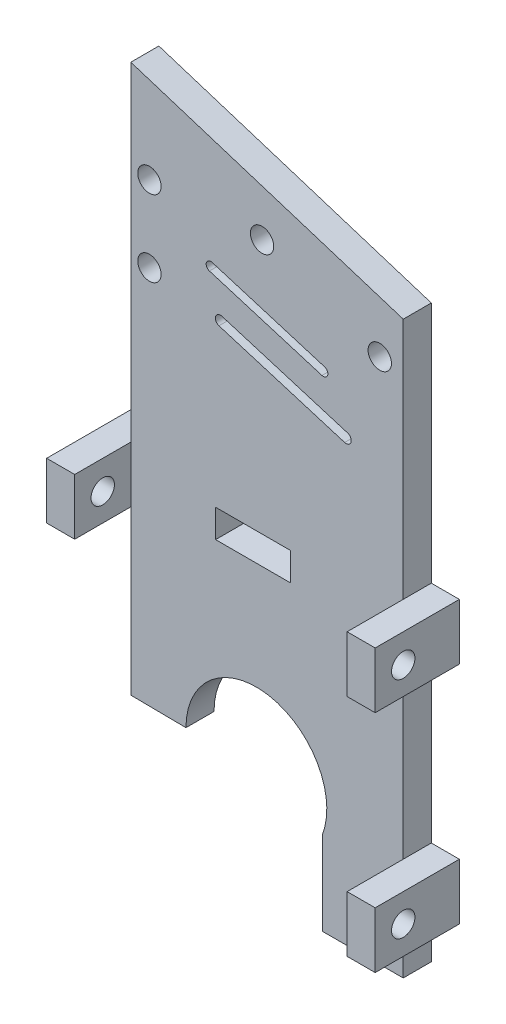
SolidWorks part; units mm, degrees
ref_plane "Front Plane" through (0, 0, 0) normal (0, 0, 1) x (1, 0, 0)
ref_plane "Top Plane" through (0, 0, 0) normal (0, 1, 0) x (1, 0, 0)
ref_plane "Right Plane" through (0, 0, 0) normal (1, 0, 0) x (0, 0, -1)
sketch "Sketch1" plane through (0, 0, 0) normal (0, 1, 0) x (1, 0, 0)
  line L1 (-50.1455, -21.689) -> (-21.0155, -21.689)
  line L2 (-50.1455, -21.689) -> (-50.1455, -23.689)
  line L3 (-50.1455, -23.689) -> (-21.0155, -23.689)
  line L4 (-21.0155, -21.689) -> (-21.0155, -23.689)
extrude "Boss-Extrude1" add sketch "Sketch1" along normal blind 45.22
sketch "Sketch15" plane through (0, 0, 0) normal (0, -1, 0) x (1, 0, 0)
  line L0 (-21.0155, 23.689) -> (-28.6855, 23.689) construction
  line L1 (-28.6855, 23.689) -> (-24.8505, 23.689) construction
  line L2 (-24.8505, 23.689) -> (-24.8505, 21.689) construction
  line L4 (-24.8505, 21.689) -> (-21.0155, 21.689) construction
  line L6 (-24.8505, 23.689) -> (-21.0155, 23.689)
  line L7 (-24.8505, 23.689) -> (-24.8505, 21.689)
  line L8 (-24.8505, 21.689) -> (-21.0155, 21.689)
  line L9 (-21.0155, 23.689) -> (-21.0155, 21.689)
extrude "Boss-Extrude7" add sketch "Sketch15" along normal blind 25.02
sketch "Sketch19" plane through (-21.0155, 0, 0) normal (1, 0, 0) x (0, 0, -1)
  line L0 (-23.689, -14.02) -> (-21.689, -14.02) construction
  line L2 (-21.689, -14.02) -> (-21.689, -20.02)
  line L3 (-23.689, -20.02) -> (-21.689, -20.02)
  line L5 (-23.689, -14.02) -> (-21.689, -14.02)
  line L6 (-23.689, -14.02) -> (-23.689, -20.02)
extrude "Boss-Extrude9" add sketch "Sketch19" along normal blind 3
sketch "Sketch20" plane through (0, 0, 21.689) normal (0, 0, -1) x (-1, 0, 0)
  line L1 (18.0155, -14.02) -> (21.0155, -14.02)
  line L2 (18.0155, -14.02) -> (18.0155, -20.02)
  line L3 (18.0155, -20.02) -> (21.0155, -20.02)
  line L4 (21.0155, -14.02) -> (21.0155, -20.02)
extrude "Boss-Extrude10" add sketch "Sketch20" along normal blind 6
sketch "Sketch24" plane through (0, 0, 23.689) normal (0, 0, 1) x (1, 0, 0)
  line L0 (-21.0155, 45.22) -> (-21.0155, 37.57) construction
  line L1 (-21.0155, 45.22) -> (-21.0155, -14.02) construction
  line L2 (-21.0155, 45.22) -> (-21.0155, 37.57)
  line L3 (-21.0155, 37.57) -> (-50.1455, 45.22)
  line L4 (-50.1455, 45.22) -> (-21.0155, 45.22)
  line L5 (-21.0155, 45.22) -> (-21.0155, -14.02) construction
  line L6 (-50.1455, 45.22) -> (-21.0155, 45.22) construction
  line L8 (-21.0155, 45.22) -> (-21.0155, 37.57) construction
extrude "Cut-Extrude10" cut sketch "Sketch24" against normal blind 4
sketch "Sketch27" plane through (0, 0, 23.689) normal (0, 0, 1) x (1, 0, 0)
  circle A0 centre (-48.1555, 35.3258) radius 1.25
  circle A1 centre (-48.1555, 27.1812) radius 1.25
extrude "Cut-Extrude13" cut sketch "Sketch27" against normal blind 5
sketch "Sketch28" plane through (0, 0, 23.689) normal (0, 0, 1) x (1, 0, 0)
  line L0 (-48.1592, 35.3258) -> (-48.1592, 27.1812) construction
  line L1 (-48.1592, 27.1812) -> (-48.1592, 31.2535) construction
  line L2 (-48.1592, 31.2535) -> (-23.5255, 31.2535) construction
  circle A0 centre (-23.5255, 31.2535) radius 1.25
sketch "Sketch32" plane through (0, 0, 23.689) normal (0, 0, 1) x (1, 0, 0)
  circle A0 centre (-36.1145, 35.7898) radius 1.25
sketch "Sketch35" plane through (0, 0, 23.689) normal (0, 0, 1) x (1, 0, 0)
  line L0 (-21.0155, 37.57) -> (-21.0155, 35.99)
  line L1 (-21.0155, 37.57) -> (-21.0155, -14.02) construction
  line L2 (-21.0155, 35.99) -> (-21.0155, 37.57)
  line L3 (-21.0155, 35.99) -> (-50.1455, 45.22)
  line L4 (-50.1455, 45.22) -> (-21.0155, 37.57)
  line M5 (-21.0155, -14.02) -> (-21.0155, 37.57)
  line M6 (-21.0155, 37.57) -> (-50.1455, 45.22)
extrude "Cut-Extrude16" cut sketch "Sketch35" against normal blind 4.86 contours L3 M5 M6
mirror "Mirror1" about plane through (0, 0, 15.689) normal (0, 0, -1) of bodies 129 130
delete or keep bodies "Body-Delete/Keep 1" type delete bodies bodies 129
sketch "Sketch37" plane through (0, 0, 7.689) normal (0, 0, -1) x (-1, 0, 0)
  line L13 (21.0155, 24.3006) -> (50.1455, 33.1563) construction
  line L14 (29.5652, 26.8997) -> (41.5958, 30.5571) construction
  line L15 (29.4224, 27.3694) -> (41.453, 31.0268)
  line L16 (29.708, 26.4301) -> (41.7386, 30.0874)
  line L17 (21.0155, 24.3006) -> (21.0155, 20.1026) construction
  line L18 (21.0155, 20.1026) -> (50.1455, 28.9583) construction
  line L19 (27.1219, 21.959) -> (40.5639, 26.0454) construction
  line L20 (26.9639, 22.4788) -> (40.4059, 26.5653)
  line L21 (27.28, 21.4391) -> (40.722, 25.5256)
  arc A0 (29.4224, 27.3694) -> (29.708, 26.4301) centre (29.5652, 26.8997) ccw
  arc A1 (41.7386, 30.0874) -> (41.453, 31.0268) centre (41.5958, 30.5571) ccw
  arc A2 (26.9639, 22.4788) -> (27.28, 21.4391) centre (27.1219, 21.959) ccw
  arc A3 (40.722, 25.5256) -> (40.4059, 26.5653) centre (40.5639, 26.0454) ccw
  point P18 (35.5805, 28.7284)
  point P27 (33.8429, 24.0022)
extrude "Cut-Extrude20" cut sketch "Sketch37" against normal blind 5
mirror "Mirror2" about plane through (0, 0, 15.689) normal (0, 0, 1) of bodies 134
delete or keep bodies "Body-Delete/Keep 2" type delete bodies bodies 134
extrude "Cut-Extrude23" cut sketch "Sketch28" against normal blind 5 contours A0
extrude "Cut-Extrude25" cut sketch "Sketch32" against normal blind 5 contours A0
sketch "Sketch38" plane through (-50.1455, 0, 0) normal (-1, 0, 0) x (0, 0, 1)
  line L0 (23.689, 4.0427) -> (23.689, 3.98) construction
  line L1 (21.689, 4.0427) -> (23.689, 4.0427)
  line L2 (21.689, 4.0427) -> (21.689, 10.0427)
  line L3 (21.689, 10.0427) -> (23.689, 10.0427)
  line L4 (23.689, 4.0427) -> (23.689, 10.0427)
  line L5 (23.689, 45.22) -> (23.689, 0) construction
  line L6 (23.689, 10.0427) -> (23.689, 9.98) construction
extrude "Boss-Extrude11" add sketch "Sketch38" along normal blind 3
sketch "Sketch39" plane through (0, 0, 21.689) normal (0, 0, -1) x (-1, 0, 0)
  line L1 (53.1455, 10.0427) -> (50.1455, 10.0427)
  line L2 (53.1455, 10.0427) -> (53.1455, 4.0427)
  line L3 (53.1455, 4.0427) -> (50.1455, 4.0427)
  line L4 (50.1455, 10.0427) -> (50.1455, 4.0427)
extrude "Boss-Extrude12" add sketch "Sketch39" along normal blind 6
sketch "Sketch40" plane through (-53.1455, 0, 0) normal (-1, 0, 0) x (0, 0, 1)
  line L0 (15.689, 4.0427) -> (15.689, 7.0427) construction
  line L1 (15.689, 4.0427) -> (15.689, 10.0427) construction
  circle A0 centre (18.689, 6.98) radius 1.25
extrude "Cut-Extrude26" cut sketch "Sketch40" against normal blind 6
sketch "Sketch51" plane through (-21.0155, 0, 0) normal (1, 0, 0) x (0, 0, -1)
  line L0 (-23.689, 4.0427) -> (-21.689, 4.0427) construction
  line L1 (-21.689, 35.99) -> (-21.689, -14.02) construction
  line L3 (-23.689, 4.0427) -> (-21.689, 4.0427)
  line L4 (-23.689, 4.0427) -> (-23.689, 10.0427)
  line L5 (-23.689, 10.0427) -> (-21.689, 10.0427)
  line L6 (-21.689, 4.0427) -> (-21.689, 10.0427)
extrude "Boss-Extrude15" add sketch "Sketch51" along normal blind 3
sketch "Sketch52" plane through (0, 0, 21.689) normal (0, 0, -1) x (-1, 0, 0)
  line L1 (18.0155, 10.0427) -> (21.0155, 10.0427)
  line L2 (18.0155, 10.0427) -> (18.0155, 4.0427)
  line L3 (18.0155, 4.0427) -> (21.0155, 4.0427)
  line L4 (21.0155, 10.0427) -> (21.0155, 4.0427)
extrude "Boss-Extrude16" add sketch "Sketch52" along normal blind 6
sketch "Sketch53" plane through (-18.0155, 0, 0) normal (1, 0, 0) x (0, 0, -1)
  line L0 (-23.689, 7.0427) -> (-15.689, 7.0427) construction
  line L1 (-23.689, 10.0427) -> (-23.689, 4.0427) construction
  line L2 (-15.689, 10.0427) -> (-15.689, 4.0427) construction
  line L3 (-15.689, 7.0427) -> (-21.689, 7.0427) construction
  circle A0 centre (-18.689, 6.98) radius 1.25
extrude "Cut-Extrude28" cut sketch "Sketch53" against normal blind 6 contours A0
mirror "Mirror4" about plane through (0, 0, 15.689) normal (0, 0, -1) of bodies 150
delete or keep bodies "Body-Delete/Keep 3" type delete bodies bodies 150
sketch "Sketch54" plane through (-18.0155, 0, 0) normal (1, 0, 0) x (0, 0, -1)
  circle A0 centre (-12.689, -17.012) radius 1.25
extrude "Cut-Extrude29" cut sketch "Sketch54" against normal blind 3
sketch "Sketch55" plane through (0, 0, 7.689) normal (0, 0, -1) x (-1, 0, 0)
  line L0 (24.8505, 0) -> (21.0155, -25.02)
  line L1 (21.0155, -25.02) -> (24.8505, -25.02)
  line L2 (24.8505, -25.02) -> (24.8505, 0)
extrude "Cut-Extrude30" cut sketch "Sketch55" against normal blind 10
sketch "Sketch56" plane through (0, 0, 9.689) normal (0, 0, 1) x (1, 0, 0)
  line L0 (-24.8505, 0) -> (-36.7178, -13.4588) construction
  line L1 (-50.1455, 0) -> (-50.1455, -13.393)
  line L2 (-50.1455, -13.393) -> (-44.2488, -13.4588)
  line L3 (-21.0155, -25.02) -> (-29.6598, -25.02)
  line L4 (-29.6598, -25.02) -> (-29.6598, -16.0856)
  circle A0 centre (-36.7178, -13.4588) radius 7.531
extrude "Boss-Extrude17" add sketch "Sketch56" against normal blind 3
sketch "Sketch57" plane through (0, 0, 7.689) normal (0, 0, -1) x (-1, 0, 0)
  line L0 (21.0155, -25.02) -> (21.0155, -20.02)
  line L1 (21.0155, -20.02) -> (18.0155, -20.02)
  line L2 (18.0155, -20.02) -> (18.0155, -14.02)
  line L3 (18.0155, -14.02) -> (21.0155, -14.02)
  line L4 (21.0155, -14.02) -> (21.0155, 4.0427)
  line L5 (21.0155, 4.0427) -> (18.0155, 4.0427)
  line L6 (18.0155, 4.0427) -> (18.0155, 10.0427)
  line L7 (18.0155, 10.0427) -> (21.0155, 10.0427)
  line L8 (21.0155, 10.0427) -> (21.0155, 35.99)
  line L9 (21.0155, 35.99) -> (50.1455, 45.22)
  line L10 (50.1455, 45.22) -> (50.1455, 10.0427)
  line L11 (50.1455, 10.0427) -> (53.1455, 10.0427)
  line L12 (53.1455, 10.0427) -> (53.1455, 4.0427)
  line L13 (53.1455, 4.0427) -> (50.1455, 4.0427)
  line L14 (50.1455, 4.0427) -> (50.1455, 0)
  line L15 (50.1455, 0) -> (24.8505, 0)
  line L16 (24.8505, 0) -> (21.0155, -25.02)
  line L17 (29.5652, 26.8997) -> (41.5958, 30.5571) construction
  line L18 (29.4229, 27.3679) -> (41.4535, 31.0253)
  line L19 (29.7075, 26.4316) -> (41.7381, 30.0889)
  line L20 (27.1219, 21.959) -> (40.5639, 26.0454) construction
  line L21 (26.964, 22.4783) -> (40.4061, 26.5648)
  line L22 (27.2798, 21.4396) -> (40.7218, 25.5261)
  circle A0 centre (23.5255, 31.2535) radius 1.25
  circle A1 centre (36.1145, 35.7898) radius 1.25
  circle A2 centre (48.1555, 35.3258) radius 1.25
  circle A3 centre (48.1555, 27.1812) radius 1.25
  arc A4 (29.4229, 27.3679) -> (29.7075, 26.4316) centre (29.5652, 26.8997) ccw
  arc A5 (41.7381, 30.0889) -> (41.4535, 31.0253) centre (41.5958, 30.5571) ccw
  arc A6 (26.964, 22.4783) -> (27.2798, 21.4396) centre (27.1219, 21.959) ccw
  arc A7 (40.7218, 25.5261) -> (40.4061, 26.5648) centre (40.5639, 26.0454) ccw
  point P50 (35.5805, 28.7284)
  point P55 (33.8429, 24.0022)
extrude "Boss-Extrude18" add sketch "Sketch57" along normal blind 1
sketch "Sketch58" plane through (0, 0, 6.689) normal (0, 0, -1) x (-1, 0, 0)
  line L0 (21.0155, 10.0427) -> (21.0155, 4.0427) construction
  line L1 (21.0155, 4.0427) -> (21.0155, 7.0427) construction
  line L2 (21.0155, 7.0427) -> (53.1455, 7.0427) construction
  line L3 (53.1455, 4.0427) -> (53.1455, 10.0427) construction
  line L4 (53.1455, 7.0427) -> (37.0805, 7.0427) construction
  line L5 (37.0805, 7.0427) -> (37.0805, 8.5427) construction
  line L6 (37.0805, 8.5427) -> (37.0805, 5.5427) construction
  line L7 (37.0805, 8.5427) -> (41.0805, 8.5427) construction
  line L8 (41.0805, 8.5427) -> (33.0805, 8.5427) construction
  line L9 (33.0805, 8.5427) -> (41.0805, 8.5427)
  line L10 (41.0805, 8.5427) -> (41.0805, 5.5427)
  line L11 (41.0805, 5.5427) -> (33.0805, 5.5427)
  line L12 (33.0805, 5.5427) -> (33.0805, 8.5427)
extrude "Cut-Extrude31" cut sketch "Sketch58" against normal blind 10
